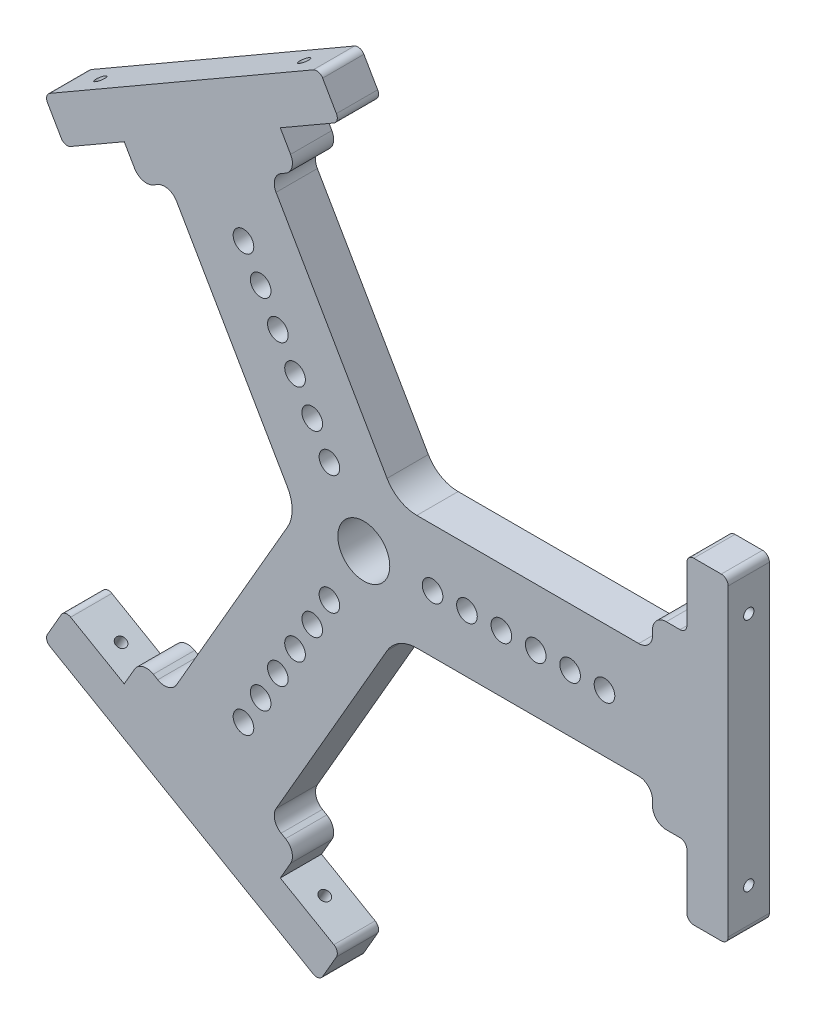
SolidWorks part; units mm, degrees
ref_plane "Plan de face" through (0, 0, 0) normal (0, 0, 1) x (1, 0, 0)
ref_plane "Plan de dessus" through (0, 0, 0) normal (0, 1, 0) x (1, 0, 0)
ref_plane "Plan de droite" through (0, 0, 0) normal (1, 0, 0) x (0, 0, -1)
sketch "Esquisse1" plane through (0, 0, 0) normal (0, 0, 1) x (1, 0, 0)
  line L0 (0, 0) -> (100, 0) construction
  line L1 (0, 0) -> (93.9693, 34.202) construction
  line L2 (93.9693, 28.202) -> (93.9693, 44.202)
  line L3 (0, 0) -> (93.9693, -34.202) construction
  line L4 (15.4211, 16.7101) -> (79.9693, 16.7101)
  line L5 (83.9693, 20.7101) -> (83.9693, 22.202)
  line L6 (87.9693, 26.202) -> (91.9693, 26.202)
  line L7 (83.9693, -20.7101) -> (83.9693, -22.202)
  line L8 (87.9693, -26.202) -> (91.9693, -26.202)
  line L9 (15.4211, -16.7101) -> (79.9693, -16.7101)
  line L10 (6.7608, -21.7101) -> (-25.5133, -77.6105)
  line L11 (-22.1819, -5) -> (-54.456, -60.9004)
  line L12 (-66.6762, -63.0826) -> (-69.6762, -68.2788)
  line L13 (-86.9967, -58.2788) -> (-6.9725, -104.4808)
  line L14 (-24.0492, -83.0746) -> (-22.7571, -83.8205)
  line L15 (-21.293, -89.2846) -> (-24.293, -94.4808)
  line L16 (-22.1819, 5) -> (-54.456, 60.9004)
  line L17 (6.7608, 21.7101) -> (-25.5133, 77.6105)
  line L18 (-21.293, 89.2846) -> (-24.293, 94.4808)
  line L19 (-6.9725, 104.4808) -> (-86.9967, 58.2788)
  line L20 (-59.9201, 62.3645) -> (-61.2121, 61.6185)
  line L21 (-66.6762, 63.0826) -> (-69.6762, 68.2788)
  line L22 (0, 0) -> (20, 0) construction
  line L26 (-61.2121, -61.6185) -> (-59.9201, -62.3645)
  line L27 (-24.0492, 83.0746) -> (-22.7571, 83.8205)
  line L28 (95.9693, 46.202) -> (103.9693, 46.202)
  line L29 (105.9693, 44.202) -> (105.9693, -44.202)
  line L30 (103.9693, -46.202) -> (95.9693, -46.202)
  line L31 (93.9693, -44.202) -> (93.9693, -28.202)
  line L32 (-14.7046, -113.8731) -> (-91.2647, -69.6711)
  line L33 (-7.9725, -106.2128) -> (-11.9725, -113.141)
  line L34 (-22.561, -95.4808) -> (-8.7046, -103.4808)
  line L35 (-85.2647, -59.2788) -> (-71.4083, -67.2788)
  line L36 (-91.9967, -66.939) -> (-87.9967, -60.0108)
  line L37 (-91.2647, 69.6711) -> (-14.7046, 113.8731)
  line L38 (-87.9967, 60.0108) -> (-91.9967, 66.939)
  line L39 (-71.4083, 67.2788) -> (-85.2647, 59.2788)
  line L40 (-8.7046, 103.4808) -> (-22.561, 95.4808)
  line L41 (-11.9725, 113.141) -> (-7.9725, 106.2128)
  circle A0 centre (0, 0) radius 100 construction
  circle A1 centre (0, 0) radius 7.55
  circle A2 centre (0, 0) radius 15
  arc A3 (83.9693, 22.202) -> (87.9693, 26.202) centre (87.9693, 22.202) cw
  arc A4 (79.9693, 16.7101) -> (83.9693, 20.7101) centre (79.9693, 20.7101) ccw
  arc A5 (83.9693, -22.202) -> (87.9693, -26.202) centre (87.9693, -22.202) ccw
  arc A6 (79.9693, -16.7101) -> (83.9693, -20.7101) centre (79.9693, -20.7101) cw
  arc A7 (-54.456, -60.9004) -> (-59.9201, -62.3645) centre (-57.9201, -58.9004) cw
  arc A8 (-61.2121, -61.6185) -> (-66.6762, -63.0826) centre (-63.2121, -65.0826) ccw
  arc A9 (-25.5133, -77.6105) -> (-24.0492, -83.0746) centre (-22.0492, -79.6105) ccw
  arc A10 (-22.7571, -83.8205) -> (-21.293, -89.2846) centre (-24.7571, -87.2846) cw
  arc A11 (-25.5133, 77.6105) -> (-24.0492, 83.0746) centre (-22.0492, 79.6105) cw
  arc A12 (-22.7571, 83.8205) -> (-21.293, 89.2846) centre (-24.7571, 87.2846) ccw
  arc A13 (-54.456, 60.9004) -> (-59.9201, 62.3645) centre (-57.9201, 58.9004) ccw
  arc A14 (-61.2121, 61.6185) -> (-66.6762, 63.0826) centre (-63.2121, 65.0826) cw
  circle A15 centre (20, 0) radius 3
  circle A16 centre (40, 0) radius 3
  circle A17 centre (60, 0) radius 3
  circle A18 centre (70, 0) radius 3
  circle A19 centre (50, 0) radius 3
  circle A20 centre (30, 0) radius 3
  circle A21 centre (-10, -17.3205) radius 3
  circle A22 centre (-15, -25.9808) radius 3
  circle A23 centre (-20, -34.641) radius 3
  circle A24 centre (-25, -43.3013) radius 3
  circle A25 centre (-30, -51.9615) radius 3
  circle A26 centre (-35, -60.6218) radius 3
  circle A27 centre (-10, 17.3205) radius 3
  circle A28 centre (-15, 25.9808) radius 3
  circle A29 centre (-20, 34.641) radius 3
  circle A30 centre (-25, 43.3013) radius 3
  circle A31 centre (-30, 51.9615) radius 3
  circle A32 centre (-35, 60.6218) radius 3
  arc A33 (15.4211, 16.7101) -> (6.7608, 21.7101) centre (15.4211, 26.7101) cw
  arc A34 (-22.1819, 5) -> (-22.1819, -5) centre (-30.8422, 0) cw
  arc A35 (15.4211, -16.7101) -> (6.7608, -21.7101) centre (15.4211, -26.7101) ccw
  arc A36 (93.9693, 28.202) -> (91.9693, 26.202) centre (91.9693, 28.202) cw
  arc A37 (95.9693, 46.202) -> (93.9693, 44.202) centre (95.9693, 44.202) ccw
  arc A38 (103.9693, 46.202) -> (105.9693, 44.202) centre (103.9693, 44.202) cw
  arc A39 (105.9693, -44.202) -> (103.9693, -46.202) centre (103.9693, -44.202) cw
  arc A40 (95.9693, -46.202) -> (93.9693, -44.202) centre (95.9693, -44.202) cw
  arc A41 (91.9693, -26.202) -> (93.9693, -28.202) centre (91.9693, -28.202) cw
  arc A42 (-11.9725, -113.141) -> (-14.7046, -113.8731) centre (-13.7046, -112.141) cw
  arc A43 (-7.9725, -106.2128) -> (-8.7046, -103.4808) centre (-9.7046, -105.2128) ccw
  arc A44 (-22.561, -95.4808) -> (-23.293, -92.7487) centre (-21.561, -93.7487) cw
  arc A45 (-68.6762, -66.5467) -> (-71.4083, -67.2788) centre (-70.4083, -65.5467) cw
  arc A46 (-87.9967, -60.0108) -> (-85.2647, -59.2788) centre (-86.2647, -61.0108) cw
  arc A47 (-91.2647, -69.6711) -> (-91.9967, -66.939) centre (-90.2647, -67.939) cw
  arc A48 (-91.9967, 66.939) -> (-91.2647, 69.6711) centre (-90.2647, 67.939) cw
  arc A49 (-87.9967, 60.0108) -> (-85.2647, 59.2788) centre (-86.2647, 61.0108) ccw
  arc A50 (-71.4083, 67.2788) -> (-68.6762, 66.5467) centre (-70.4083, 65.5467) cw
  arc A51 (-23.293, 92.7487) -> (-22.561, 95.4808) centre (-21.561, 93.7487) cw
  arc A52 (-7.9725, 106.2128) -> (-8.7046, 103.4808) centre (-9.7046, 105.2128) cw
  arc A53 (-14.7046, 113.8731) -> (-11.9725, 113.141) centre (-13.7046, 112.141) cw
  point P15 (83.9693, 26.202)
  point P66 (0, 0)
  point P111 (93.9693, 46.202)
  point P114 (105.9693, 46.202)
  point P160 (0, 0)
  dimension "D1" = 200
  dimension "D6" = 15.1
  dimension "D7" = 30
  dimension "D10" = 4
  dimension "D11" = 4
  dimension "D13" = 6
  dimension "D14" = 6
  dimension "D15" = 6
  dimension "D16" = 6
  dimension "D17" = 6
  dimension "D18" = 6
  dimension "D27" = 10
  dimension "D28" = 10
  dimension "D4" = 2
  dimension "D9" = 2
  dimension "D2" = 20
  dimension "D3" = 12
  dimension "D5" = 20
  dimension "D8" = 10
  dimension "D19" = 10
  dimension "D20" = 10
  dimension "D21" = 10
  dimension "D22" = 10
  dimension "D23" = 10
  dimension "D24" = 20
  dimension "D26" = 20
  dimension "D29" = 12
  dimension "D12" = 3
  dimension "D25" = 3
  dimension "D30" = 3
extrude "Boss.-Extru.1" add sketch "Esquisse1" along normal mid plane 12 contours A35 L9 A6 L7 A5 L8 L2 L6 A3 L5 A4 L4 A33 L17 A11 L27 A12 L18 L19 L21 A14 L20 A13 L16 A34 L11 A7 L26 A8 L12 L13 L15 A10 L14 A9 L10 A32 A31 A30 A29 A28 A27 A26 | A2 A1 | A53 L37 A48 L38 A49 L19 A52 L41 | A47 L32 A42 L33 A43 L13 A46 L36
sketch "Esquisse2" plane through (93.9693, 0, 0) normal (-1, 0, 0) x (0, 0, 1)
  circle A0 centre (0, 34.202) radius 1.5
  circle A1 centre (0, -34.202) radius 1.5
  dimension "D1" = 3
  dimension "D2" = 3
extrude "Enlèv. mat.-Extru.1" cut sketch "Esquisse2" against normal through all
pattern_circular "Répétition circulaire1" count 3 every 120 about axis through (0, 0, 6) along (0, 0, -1) of "Enlèv. mat.-Extru.1"
sketch "Esquisse3" plane through (0, 0, 0) normal (0, 0, 1) x (1, 0, 0)
  point P0 (0, 0)
equation "\"D14@Esquisse1\"=\"D13@Esquisse1\""
equation "\"D15@Esquisse1\"=\"D13@Esquisse1\""
equation "\"D16@Esquisse1\"=\"D13@Esquisse1\""
equation "\"D17@Esquisse1\"=\"D13@Esquisse1\""
equation "\"D18@Esquisse1\"=\"D13@Esquisse1\""
equation "\"D20@Esquisse1\"=\"D19@Esquisse1\""
